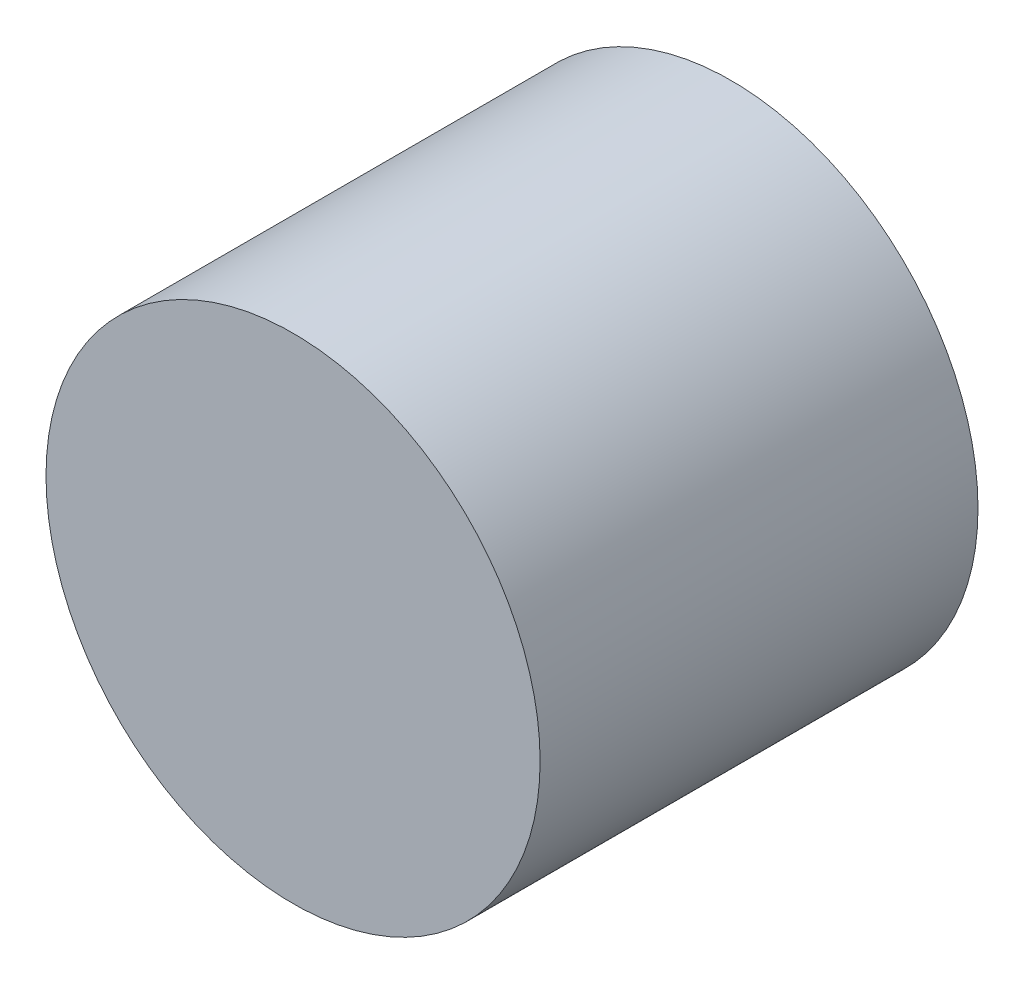
SolidWorks part; units mm, degrees
ref_plane "Front Plane" through (0, 0, 0) normal (1, 0, 0) x (0, 1, 0)
ref_plane "Top Plane" through (0, 0, 0) normal (0, 0, 1) x (0, 1, 0)
ref_plane "Right Plane" through (0, 0, 0) normal (0, 1, 0) x (-1, 0, 0)
sketch "Sketch1" plane through (0, 0, 0) normal (0, 0, 1) x (0, 1, 0)
  circle A0 centre (0, 0) radius 12.6111
  dimension "D1" = 25.2222
extrude "Boss-Extrude1" add sketch "Sketch1" along normal blind 22.352
